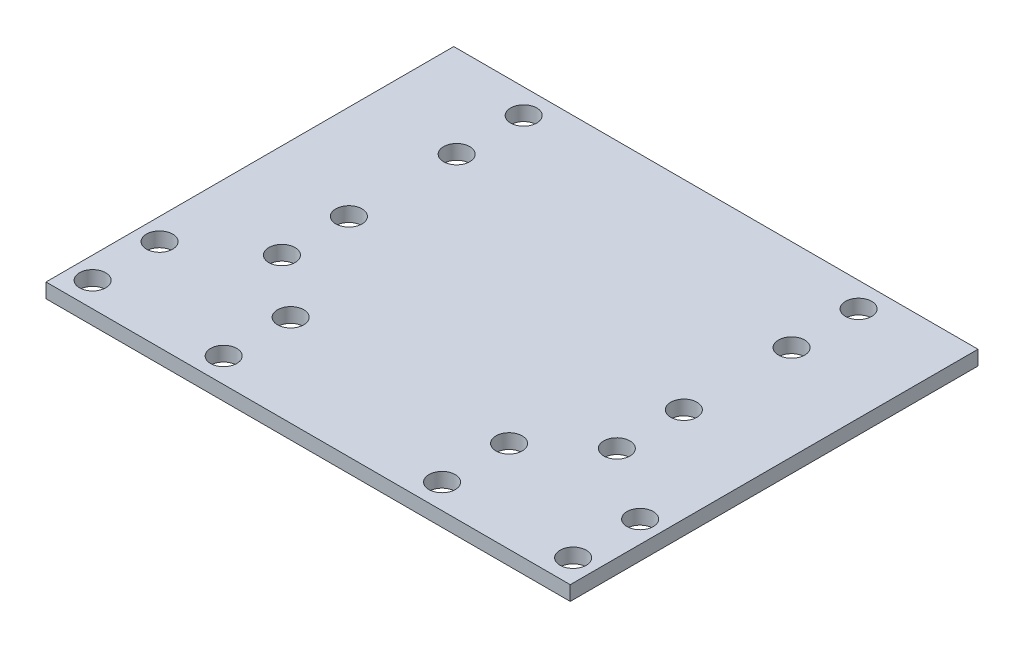
SolidWorks part; units mm, degrees
ref_plane "Front Plane" through (0, 0, 0) normal (0, 0, 1) x (1, 0, 0)
ref_plane "Top Plane" through (0, 0, 0) normal (0, 1, 0) x (1, 0, 0)
ref_plane "Right Plane" through (0, 0, 0) normal (1, 0, 0) x (0, 0, -1)
sketch "Sketch1" plane through (0, 0, 0) normal (0, 1, 0) x (1, 0, 0)
  line L1 (90, -70) -> (-90, -70)
  line L2 (90, -70) -> (90, 70)
  line L3 (90, 70) -> (-90, 70)
  line L4 (-90, -70) -> (-90, 70)
  line L5 (90, -70) -> (-90, 70) construction
  line L6 (90, 70) -> (-90, -70) construction
  point P0 (0, 0)
  dimension "D1" = 180
  dimension "D2" = 140
extrude "Body" add sketch "Sketch1" along normal blind 5
sketch "Sketch2" plane through (0, 5, 0) normal (0, 1, 0) x (1, 0, 0)
  line L0 (0, -1000) -> (0, 49000) construction
  circle A0 centre (-57.5, 61.5) radius 4.5
  circle A1 centre (-57.5, 38.5) radius 4.5
  circle A2 centre (-57.5, 1.5) radius 4.5
  circle A3 centre (-57.5, -21.5) radius 4.5
  circle A4 centre (-82.5, -38.5) radius 4.5
  circle A5 centre (-82.5, -61.5) radius 4.5
  circle A6 centre (-37.5, -61.5) radius 4.5
  circle A7 centre (-37.5, -38.5) radius 4.5
  circle A8 centre (37.5, -38.5) radius 4.5
  circle A9 centre (37.5, -61.5) radius 4.5
  circle A10 centre (82.5, -61.5) radius 4.5
  circle A11 centre (82.5, -38.5) radius 4.5
  circle A12 centre (57.5, -21.5) radius 4.5
  circle A13 centre (57.5, 1.5) radius 4.5
  circle A14 centre (57.5, 38.5) radius 4.5
  circle A15 centre (57.5, 61.5) radius 4.5
  dimension "D1" = 9
extrude "Holes" cut sketch "Sketch2" against normal through all
